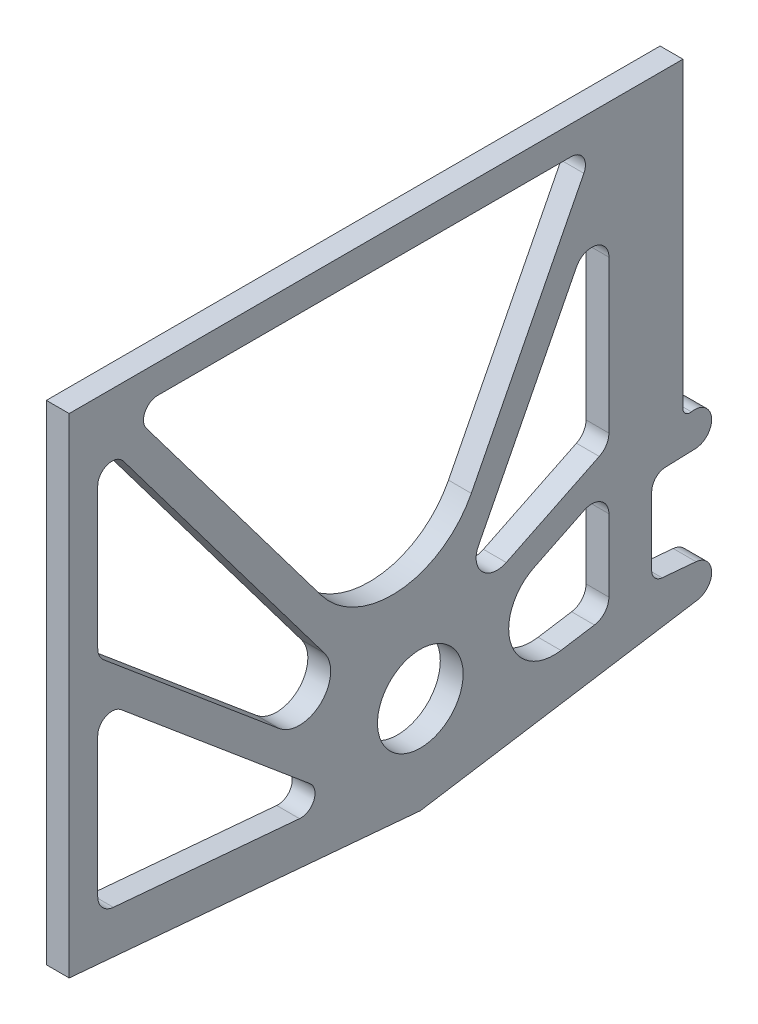
SolidWorks part; units mm, degrees
material "1023 Carbon Steel Sheet (SS)"
ref_plane "Спереди" through (0, 0, 0) normal (0, 0, 1) x (1, 0, 0)
ref_plane "Сверху" through (0, 0, 0) normal (0, 1, 0) x (1, 0, 0)
ref_plane "Справа" through (0, 0, 0) normal (1, 0, 0) x (0, 0, -1)
other "Configuration Table"
sketch "Sketch2" plane through (0, 0, 0) normal (1, 0, 0) x (0, 0, -1)
  line L0 (-769.0851, 14.2159) -> (1403.3589, 14.2159) construction
  line L1 (0, -34) -> (-123, -23.2389)
  line L2 (-123, 148) -> (92, 148)
  line L3 (-123, 148) -> (-123, -23.2389)
  line L6 (0, -34) -> (97, -18.6367)
  line L7 (0, 9.7878) -> (0, -76.711) construction
  line L8 (-113, -3.5585) -> (-113, 45.221)
  line L9 (-104.7861, 49.0512) -> (-38.667, -6.4293)
  line L10 (-42.3167, -15.2405) -> (-107.5229, -9.5357)
  line L11 (-113, 71.7954) -> (-113, 121.0542)
  line L14 (-91.9591, 138) -> (52.8427, 138)
  line L15 (57.2977, 130.73) -> (17.8728, 53.3544)
  line L16 (-34.7343, 48.7519) -> (-95.9523, 129.9909)
  line L17 (-104.0068, 124.0632) -> (-33.6119, 30.646)
  line L18 (-49.4183, 15.6462) -> (-110.8567, 67.1992)
  line L19 (66.0614, 100.9111) -> (66.0614, 47.5378)
  line L20 (62.6916, 42.145) -> (30.1096, 26.2537)
  line L21 (20.3486, 36.1866) -> (54.7154, 103.635)
  line L22 (66.0614, 23.0605) -> (66.0614, -2.213)
  line L23 (61, -8.1391) -> (49.2707, -9.9968)
  line L24 (39.8509, 19.8788) -> (57.4312, 28.4533)
  line L25 (92, 148) -> (92, 42)
  line L26 (96.2701, 27.6483) -> (85.8875, 27.287)
  line L27 (81.0614, 22.29) -> (81.0614, -1.71)
  line L28 (84.7128, -5.6948) -> (96.5843, -6.7334)
  circle A0 centre (0, 0) radius 30 construction
  circle A1 centre (0, 0) radius 15
  arc A2 (17.8728, 53.3544) -> (-34.7343, 48.7519) centre (-9.8687, 67.4894) cw
  arc A3 (-33.6119, 30.646) -> (-49.4183, 15.6462) centre (-42.3696, 24.0466) cw
  arc A4 (30.1096, 26.2537) -> (20.3486, 36.1866) centre (26.8909, 32.8531) cw
  arc A5 (49.2707, -9.9968) -> (39.8509, 19.8788) centre (46.7933, 5.6449) cw
  arc A6 (-38.667, -6.4293) -> (-42.3167, -15.2405) centre (-41.8809, -10.2595) cw
  arc A7 (-113, 45.221) -> (-104.7861, 49.0512) centre (-108, 45.221) cw
  arc A8 (66.0614, 100.9111) -> (54.7154, 103.635) centre (60.0614, 100.9111) ccw
  arc A9 (-91.9591, 138) -> (-95.9523, 129.9909) centre (-91.9591, 133) ccw
  arc A10 (52.8427, 138) -> (57.2977, 130.73) centre (52.8427, 133) cw
  arc A11 (-113, 121.0542) -> (-104.0068, 124.0632) centre (-108, 121.0542) cw
  arc A12 (66.0614, 23.0605) -> (57.4312, 28.4533) centre (60.0614, 23.0605) ccw
  arc A13 (66.0614, 47.5378) -> (62.6916, 42.145) centre (60.0614, 47.5378) cw
  arc A14 (66.0614, -2.213) -> (61, -8.1391) centre (60.0614, -2.213) cw
  arc A15 (-113, 71.7954) -> (-110.8567, 67.1992) centre (-107, 71.7954) ccw
  arc A16 (-113, -3.5585) -> (-107.5229, -9.5357) centre (-107, -3.5585) ccw
  arc A17 (92, 42) -> (94.9592, 39.5425) centre (94.5, 42) ccw
  arc A18 (94.9592, 39.5425) -> (96.2701, 27.6483) centre (96.0614, 33.6446) cw
  arc A19 (85.8875, 27.287) -> (81.0614, 22.29) centre (86.0614, 22.29) ccw
  arc A20 (81.0614, -1.71) -> (84.7128, -5.6948) centre (85.0614, -1.71) ccw
  arc A21 (96.5843, -6.7334) -> (97, -18.6367) centre (96.0614, -12.7106) cw
  point P60 (-113, 55.9435)
  point P65 (-101.9876, 138)
  point P68 (61.0019, 138)
  point P71 (-113, 135.9976)
  point P74 (66.0614, 32.6625)
  point P77 (66.0614, 43.7886)
  point P80 (66.0614, -7.3375)
  point P83 (-113, 68.9976)
  point P86 (-113, -9.0565)
  dimension "D1" = 60
  dimension "D8" = 15
  dimension "D31" = 5
  dimension "D32" = 6
  dimension "D33" = 5
  dimension "D34" = 5
  dimension "D35" = 6
  dimension "D36" = 6
  dimension "D38" = 6
  dimension "D39" = 5
  dimension "D40" = 4
  dimension "D43" = 2.5
  dimension "D2" = 123
  dimension "D4" = 148
  dimension "D5" = 85
  dimension "D6" = 81
  dimension "D7" = 34
  dimension "D9" = 10
  dimension "D10" = 215
  dimension "D11" = 10
  dimension "D12" = 10
  dimension "D13" = 10
  dimension "D14" = 10
  dimension "D15" = 10
  dimension "D16" = 15
  dimension "D17" = 50
  dimension "D18" = 65
  dimension "D19" = 67
  dimension "D20" = 37
  dimension "D21" = 97
  dimension "D22" = 40
  dimension "D23" = 16
  dimension "D24" = 17
  dimension "D25" = 64
  dimension "D26" = 83
  dimension "D27" = 63
  dimension "D28" = 95
  dimension "D29" = 111.7508
  dimension "D30" = 40
  dimension "D37" = 106
  dimension "D41" = 24
  dimension "D42" = 21
  dimension "D44" = 15
extrude "frame" add sketch "Sketch2" along normal blind 8
sketch "Sketch3" plane through (8, 0, 0) normal (1, 0, 0) x (0, 0, -1)
  line L0 (-118, 141.3117) -> (-118, -10.2599) construction
  line L1 (-113, 121.0542) -> (-113, 71.7954) construction
  line L2 (-123, 148) -> (-123, -23.2389) construction
  line L3 (71.0614, 134.6943) -> (71.0614, -7.1333) construction
  line L6 (66.0614, 47.5378) -> (66.0614, 100.9111) construction
  circle A0 centre (-117, 122) radius 3
  circle A1 centre (-119, 110) radius 3
  circle A2 centre (72.0614, 122) radius 3
  circle A3 centre (70.0614, 110) radius 3
  circle A4 centre (-117, 0) radius 3
  circle A5 centre (-119, -12) radius 3
  circle A6 centre (72.0614, 0) radius 3
  circle A7 centre (70.0614, -12) radius 3
  dimension "D1" = 6
  dimension "D2" = 1
  dimension "D3" = 1
  dimension "D4" = 12
  dimension "D5" = 110
  dimension "D6" = 1
  dimension "D7" = 1
  dimension "D8" = 12
  dimension "D9" = 1
  dimension "D10" = 1
  dimension "D11" = 5
extrude "pins" [suppressed] add sketch "Sketch3" along normal blind 10
fillet "Fillet1" [suppressed] radius 1
sketch "outer_stator_dia" plane through (8, 0, 0) normal (1, 0, 0) x (0, 0, -1)
  circle A0 centre (0, 0) radius 30
  dimension "D1" = 60
equation "\"D8@Sketch3\"=\"D4@Sketch3\""
